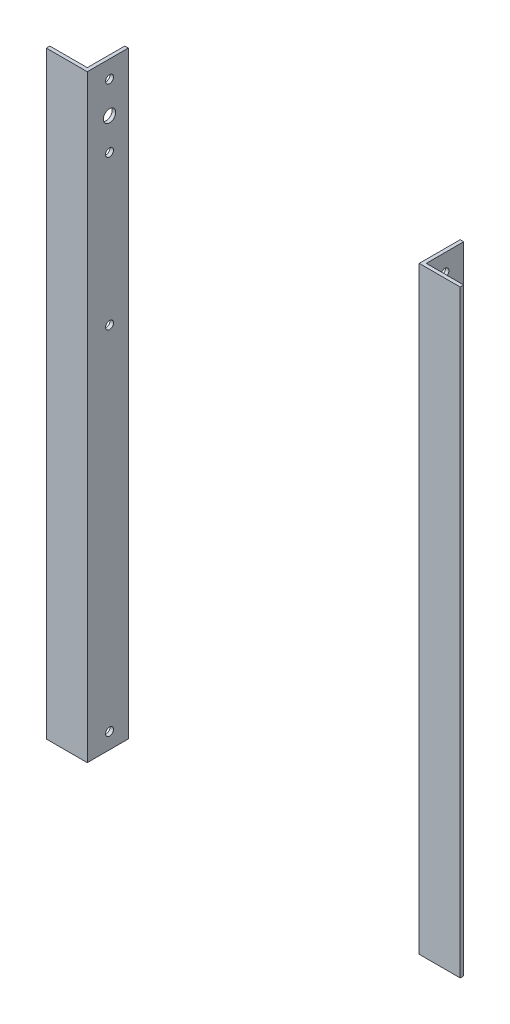
SolidWorks part; units mm, degrees
ref_plane "Front Plane" through (0, 0, 0) normal (0, 0, 1) x (1, 0, 0)
ref_plane "Top Plane" through (0, 0, 0) normal (0, 1, 0) x (1, 0, 0)
ref_plane "Right Plane" through (0, 0, 0) normal (1, 0, 0) x (0, 0, -1)
sketch "Sketch1" plane through (0, 0, 0) normal (0, 1, 0) x (1, 0, 0)
  line L0 (0, 87.7833) -> (188.6, 87.7833) construction
  line L1 (0, 87.7833) -> (0, 0) construction
  line L2 (0, 0) -> (188.6, 0) construction
  line L3 (188.6, 87.7833) -> (188.6, 0) construction
  line L4 (188.6, 0) -> (188.6, 23.3)
  line L5 (188.6, 23.3) -> (190.6, 23.3)
  line L6 (190.6, 23.3) -> (190.6, 2)
  line L7 (190.6, 2) -> (211.9, 2)
  line L8 (211.9, 2) -> (211.9, 0)
  line L9 (211.9, 0) -> (188.6, 0)
  line L10 (94.3, 87.7833) -> (94.3, 0) construction
  line L11 (-23.3, 2) -> (-23.3, 0)
  line L12 (0, 23.3) -> (-2, 23.3)
  line L13 (-2, 23.3) -> (-2, 2)
  line L14 (0, 0) -> (0, 23.3)
  line L15 (-23.3, 0) -> (0, 0)
  line L16 (-2, 2) -> (-23.3, 2)
  dimension "D1" = 188.6
  dimension "D2" = 23.3
  dimension "D3" = 2
extrude "Boss-Extrude1" add sketch "Sketch1" along normal blind 340
sketch "Sketch2" plane through (190.6, 0, 0) normal (1, 0, 0) x (0, 0, -1)
  line L0 (12.65, 0) -> (12.65, 9) construction
  line L1 (2, 0) -> (23.3, 0) construction
  circle A0 centre (12.65, 9) radius 2.25
  dimension "D2" = 4.5
  dimension "D1" = 9
extrude "Cut-Extrude1" cut sketch "Sketch2" against normal blind 215
sketch "Sketch3" plane through (190.6, 0, 0) normal (1, 0, 0) x (0, 0, -1)
  line L0 (12.65, 9) -> (12.65, 209) construction
  circle A0 centre (12.65, 209) radius 2.25
  dimension "D2" = 4.5
  dimension "D1" = 200
extrude "Cut-Extrude2" cut sketch "Sketch3" against normal blind 215
sketch "Sketch4" plane through (-2, 0, 0) normal (-1, 0, 0) x (0, 0, 1)
  line L0 (-12.65, 340) -> (-12.65, 330) construction
  line L1 (-23.3, 340) -> (-2, 340) construction
  line L2 (-12.65, 330) -> (-12.65, 312) construction
  line L3 (-12.65, 312) -> (-12.65, 294) construction
  circle A0 centre (-12.65, 330) radius 2.25
  circle A1 centre (-12.65, 294) radius 2.25
  circle A2 centre (-12.65, 312) radius 3.5
  dimension "D4" = 4.5
  dimension "D5" = 4.5
  dimension "D6" = 7
  dimension "D1" = 10
  dimension "D2" = 18
  dimension "D3" = 18
extrude "Cut-Extrude3" cut sketch "Sketch4" against normal blind 199
